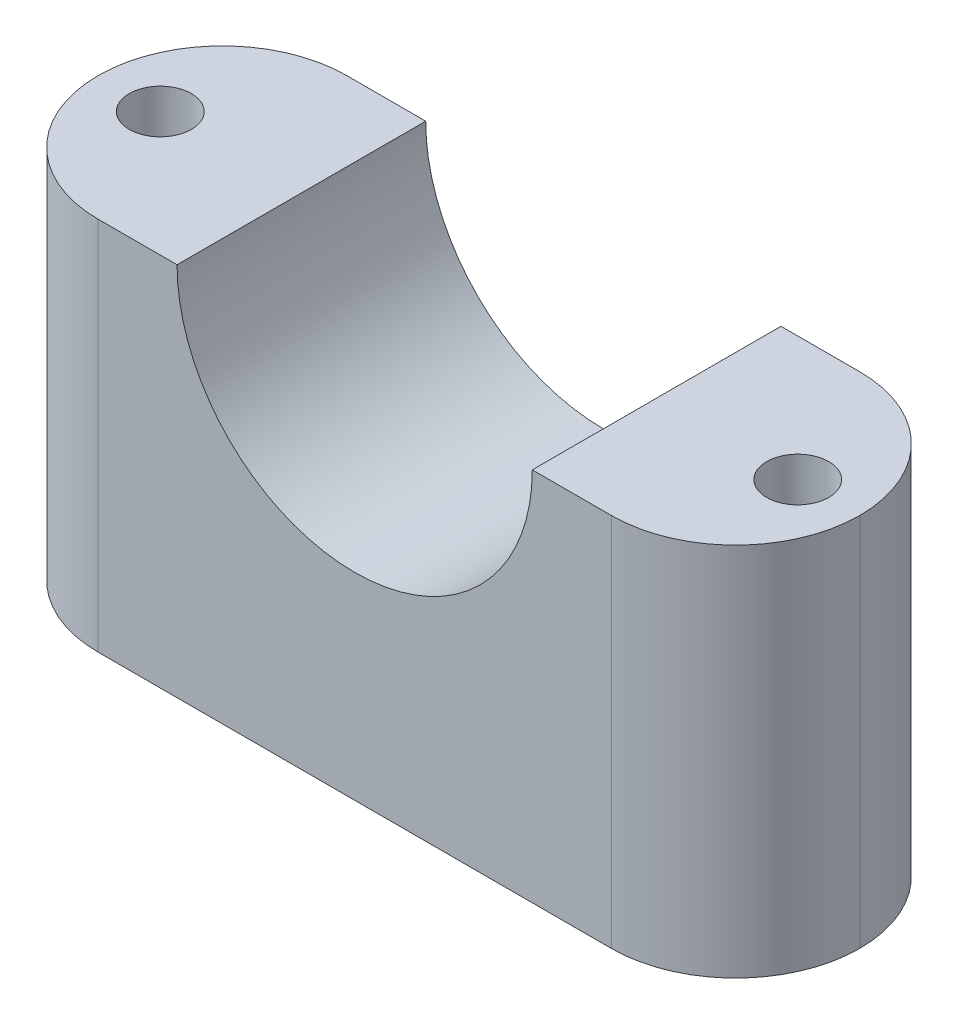
SolidWorks part; units mm, degrees
ref_plane "Front Plane" through (0, 0, 0) normal (0, 0, 1) x (1, 0, 0)
ref_plane "Top Plane" through (0, 0, 0) normal (0, 1, 0) x (1, 0, 0)
ref_plane "Right Plane" through (0, 0, 0) normal (1, 0, 0) x (0, 0, -1)
sketch "Sketch1" plane through (0, 0, 0) normal (0, 1, 0) x (1, 0, 0)
  line L0 (8, 16.002) -> (8, 0) construction
  line L1 (7.9985, 0) -> (41.0215, 0)
  line L2 (0, 7.9985) -> (0, 8.0035)
  line L3 (7.9985, 16.002) -> (41.0215, 16.002)
  line L4 (49.02, 7.9985) -> (49.02, 8.0035)
  line L5 (41.02, 16.002) -> (41.02, 0) construction
  line L6 (-4.2297, 8.001) -> (54.4165, 8.001) construction
  circle A0 centre (4, 8.001) radius 2
  circle A1 centre (45.02, 8.001) radius 2
  arc A2 (41.0215, 0) -> (49.02, 7.9985) centre (41.0215, 7.9985) ccw
  arc A3 (49.02, 8.0035) -> (41.0215, 16.002) centre (41.0215, 8.0035) ccw
  arc A4 (7.9985, 16.002) -> (0, 8.0035) centre (7.9985, 8.0035) ccw
  arc A5 (0, 7.9985) -> (7.9985, 0) centre (7.9985, 7.9985) ccw
  point P17 (49.02, 0)
  point P20 (49.02, 16.002)
  point P23 (0, 16.002)
  point P26 (0, 0)
  dimension "D5" = 4
  dimension "D7" = 7.9985
  dimension "D1" = 16.002
  dimension "D2" = 49.02
  dimension "D3" = 33.02
  dimension "D4" = 8
  dimension "D6" = 4
extrude "Boss-Extrude1" add sketch "Sketch1" along normal blind 24.13
sketch "Sketch2" plane through (0, 0, 0) normal (0, 0, 1) x (1, 0, 0)
  line L0 (24.51, 24.13) -> (24.51, 0) construction
  line L1 (7.9985, 24.13) -> (41.0215, 24.13) construction
  line L2 (7.9985, 0) -> (41.0215, 0) construction
  circle A0 centre (24.51, 24.13) radius 11.43
extrude "Cut-Extrude1" cut sketch "Sketch2" against normal through all
